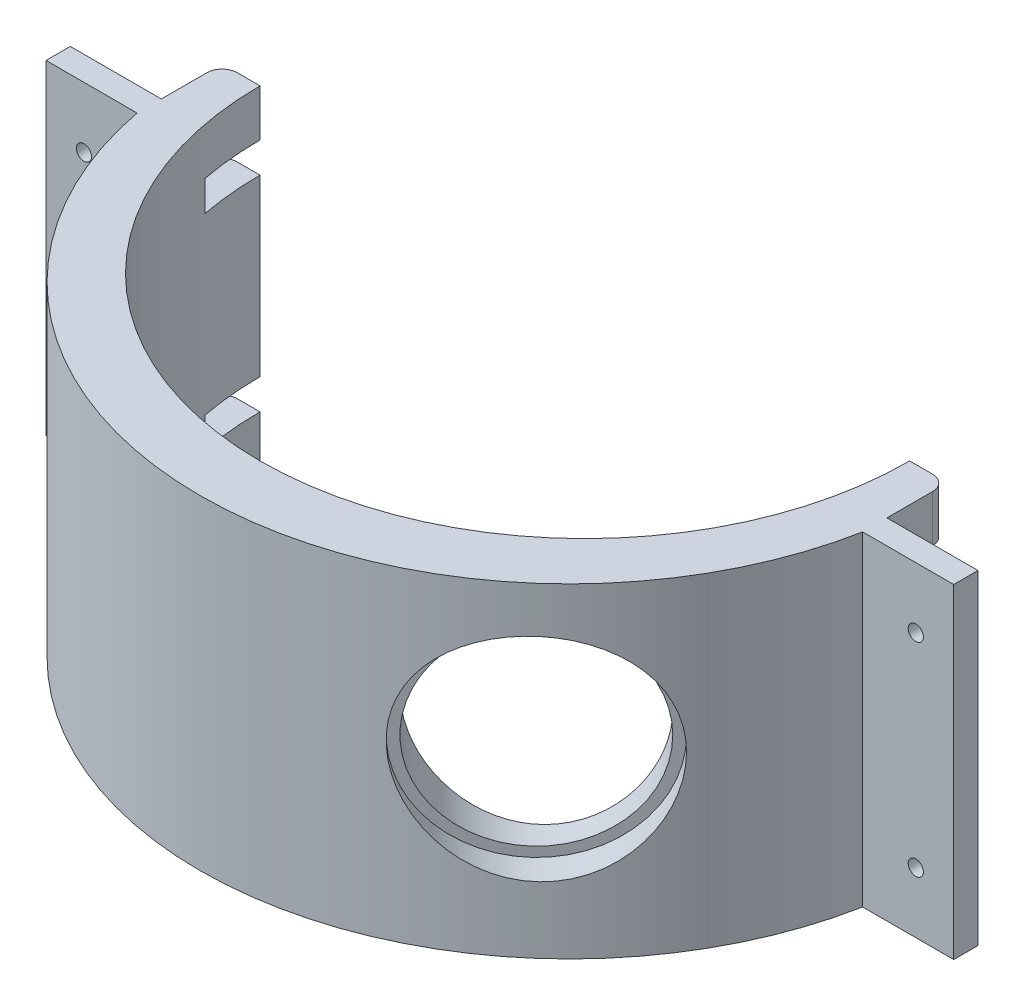
SolidWorks part; units mm, degrees
ref_plane "Front Plane" through (0, 0, 0) normal (0, 0, 1) x (1, 0, 0)
ref_plane "Top Plane" through (0, 0, 0) normal (0, 1, 0) x (1, 0, 0)
ref_plane "Right Plane" through (0, 0, 0) normal (1, 0, 0) x (0, 0, -1)
sketch "Sketch1" plane through (0, 0, 0) normal (0, 1, 0) x (1, 0, 0)
  line L0 (0, 0) -> (0, -8)
  line L1 (0, -8) -> (30, -8)
  line L2 (0, 0) -> (30, 0)
  line L3 (30, 0) -> (30, 15)
  line L4 (35, 20) -> (42.5, 20)
  line L5 (269, -8) -> (299, -8)
  line L6 (299, -8) -> (299, 0)
  line L7 (299, 0) -> (269, 0)
  line L8 (269, 0) -> (269, 15)
  line L9 (264, 20) -> (256.5, 20)
  arc A0 (30, -8) -> (269, -8) centre (149.5, 14.9181) ccw
  arc A1 (42.5, 20) -> (256.5, 20) centre (149.5, 20) ccw
  arc A2 (269, 15) -> (264, 20) centre (264, 15) ccw
  arc A3 (30, 15) -> (35, 20) centre (35, 15) cw
  dimension "D1" = 107
  dimension "D2" = 30
  dimension "D3" = 5
  dimension "D9" = 8
  dimension "D4" = 12.5
  dimension "D5" = 12.5
  dimension "D6" = 20
  dimension "D7" = 20
  dimension "D8" = 214
  dimension "D10" = 30
extrude "Boss-Extrude1" add sketch "Sketch1" along normal blind 107
sketch "Sketch2" plane through (0, 0, 0) normal (0, 0, -1) x (-1, 0, 0)
  line L1 (-269, 107) -> (-299, 107) construction
  line L2 (0, 0) -> (-30, 0) construction
  line L3 (-269, 0) -> (-299, 0) construction
  line L5 (-299, 107) -> (-299, 0) construction
  line L6 (-30, 107) -> (0, 107) construction
  circle A0 centre (-286.5, 87) radius 2.5
  circle A1 centre (-286.5, 20) radius 2.5
  circle A2 centre (-12.5, 87) radius 2.5
  circle A3 centre (-12.5, 20) radius 2.5
  dimension "D1" = 5
  dimension "D2" = 274
  dimension "D3" = 20
  dimension "D4" = 20
  dimension "D5" = 20
  dimension "D6" = 20
  dimension "D8" = 12.5
extrude "Cut-Extrude1" cut sketch "Sketch2" against normal through all
ref_plane "Plane1" through (152.699, 0, 153.5193) normal (0.7052, 0, 0.709) x (0.709, 0, -0.7052)
sketch "Sketch3" plane through (152.699, 0, 153.5193) normal (0.7052, 0, 0.709) x (0.709, 0, -0.7052)
  circle A0 centre (109.1096, 56.8658) radius 35
  dimension "D1" = 70
extrude "Cut-Extrude2" cut sketch "Sketch3" against normal blind 10 contours A0
sketch "Sketch4" plane through (145.6469, 0, 146.4293) normal (0.7052, 0, 0.709) x (0.709, 0, -0.7052)
  circle A0 centre (109.1096, 56.8658) radius 31.7783
extrude "Cut-Extrude3" cut sketch "Sketch4" against normal blind 25
sketch "Sketch5" plane through (0, 0, 0) normal (0, 0, -1) x (-1, 0, 0)
  line L1 (-269, 91.5355) -> (-253.4572, 91.5355)
  line L2 (-269, 91.5355) -> (-269, 81.5355)
  line L3 (-269, 81.5355) -> (-253.4572, 81.5355)
  line L4 (-253.4572, 91.5355) -> (-253.4572, 81.5355)
  line L5 (-269, 91.5355) -> (-253.4572, 81.5355) construction
  line L6 (-269, 81.5355) -> (-253.4572, 91.5355) construction
  line L7 (-269, 107) -> (-269, 0) construction
  line L8 (-269, 24.0087) -> (-250.3633, 24.0087)
  line L9 (-269, 24.0087) -> (-269, 14.0087)
  line L10 (-269, 14.0087) -> (-250.3633, 14.0087)
  line L11 (-250.3633, 24.0087) -> (-250.3633, 14.0087)
  line L12 (-269, 24.0087) -> (-250.3633, 14.0087) construction
  line L13 (-269, 14.0087) -> (-250.3633, 24.0087) construction
  line L14 (-149.5, 107) -> (-149.5, -6.1921) construction
  line L15 (-42.5, 107) -> (-256.5, 107) construction
  line L16 (-30, 81.5355) -> (-45.5428, 91.5355) construction
  line L17 (-30, 91.5355) -> (-45.5428, 81.5355) construction
  line L18 (-30, 14.0087) -> (-48.6367, 24.0087) construction
  line L19 (-30, 24.0087) -> (-48.6367, 14.0087) construction
  line L20 (-48.6367, 24.0087) -> (-48.6367, 14.0087)
  line L21 (-30, 14.0087) -> (-48.6367, 14.0087)
  line L22 (-30, 24.0087) -> (-30, 14.0087)
  line L23 (-30, 24.0087) -> (-48.6367, 24.0087)
  line L24 (-45.5428, 91.5355) -> (-45.5428, 81.5355)
  line L25 (-30, 91.5355) -> (-30, 81.5355)
  line L26 (-30, 91.5355) -> (-45.5428, 91.5355)
  line L27 (-30, 81.5355) -> (-45.5428, 81.5355)
  point P0 (-261.2286, 86.5355)
  point P7 (-259.6816, 19.0087)
  point P22 (-37.7714, 86.5355)
  point P27 (-39.3184, 19.0087)
  dimension "D1" = 67.5445
  dimension "D2" = 10
  dimension "D3" = 10
extrude "Cut-Extrude4" cut sketch "Sketch5" along normal up to surface (20 mm away) up to face at (260.25, 53.5, -20)
